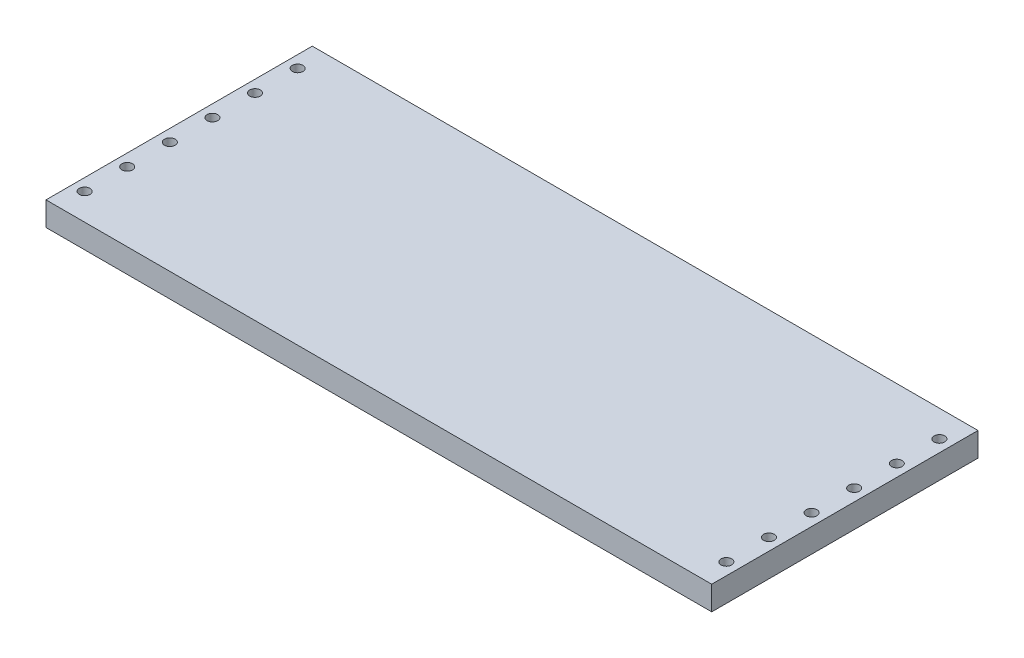
SolidWorks part; units mm, degrees
ref_plane "Front Plane" through (0, 0, 0) normal (0, 0, 1) x (1, 0, 0)
ref_plane "Top Plane" through (0, 0, 0) normal (0, 1, 0) x (1, 0, 0)
ref_plane "Right Plane" through (0, 0, 0) normal (1, 0, 0) x (0, 0, -1)
sketch "Sketch1" plane through (0, 0, 0) normal (0, 1, 0) x (1, 0, 0)
  line L1 (0, 0) -> (500, 0)
  line L2 (0, 0) -> (0, 200)
  line L3 (0, 200) -> (500, 200)
  line L4 (500, 0) -> (500, 200)
  dimension "D1" = 500
  dimension "D2" = 200
extrude "Boss-Extrude1" add sketch "Sketch1" along normal blind 18
sketch "Sketch2" plane through (0, 18, 0) normal (0, 1, 0) x (1, 0, 0)
  line L0 (9, 0) -> (9, 200) construction
  line L1 (0, 0) -> (500, 0) construction
  line L2 (500, 200) -> (0, 200) construction
  line L3 (0, 200) -> (0, 0) construction
  line L4 (250, 200) -> (250, 0) construction
  line L5 (491, 0) -> (491, 200) construction
  circle A0 centre (9, 180) radius 4
  circle A1 centre (9, 148) radius 4
  circle A2 centre (9, 116) radius 4
  circle A3 centre (9, 84) radius 4
  circle A4 centre (9, 52) radius 4
  circle A5 centre (9, 20) radius 4
  circle A6 centre (491, 20) radius 4
  circle A7 centre (491, 52) radius 4
  circle A8 centre (491, 84) radius 4
  circle A9 centre (491, 116) radius 4
  circle A10 centre (491, 148) radius 4
  circle A11 centre (491, 180) radius 4
  dimension "D2" = 8
  dimension "D3" = 20
  dimension "D1" = 9
  dimension "D4" = 6
extrude "Cut-Extrude1" cut sketch "Sketch2" against normal blind 10
